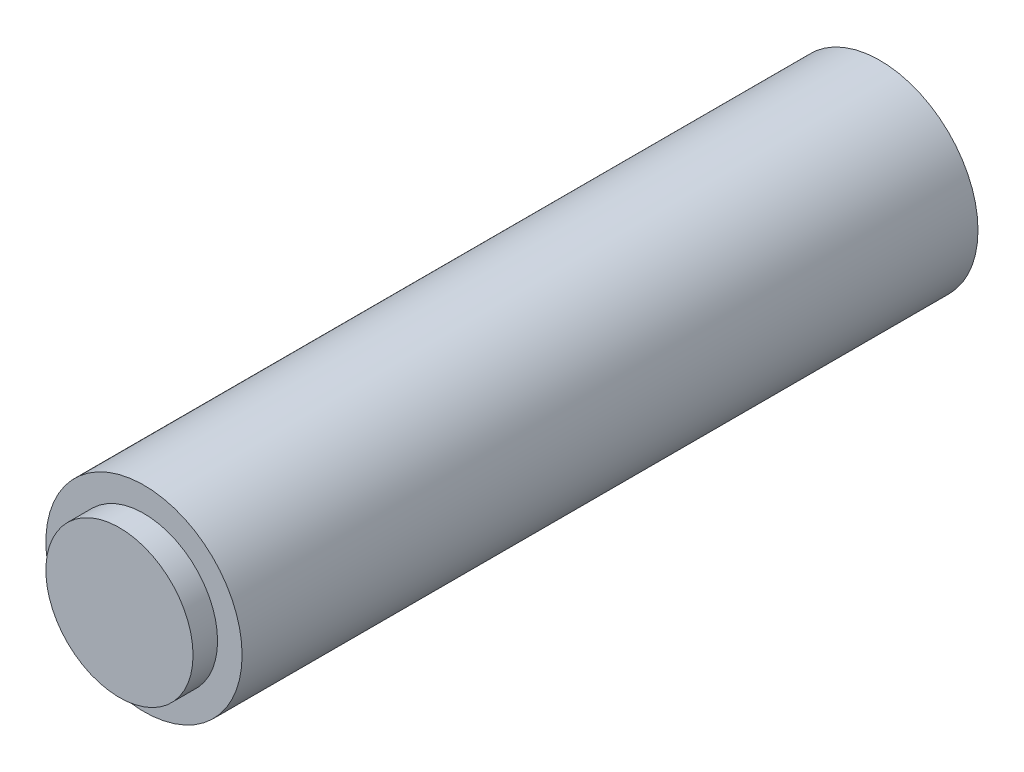
SolidWorks part; units mm, degrees
ref_plane "Спереди" through (0, 0, 0) normal (0, 0, 1) x (1, 0, 0)
ref_plane "Сверху" through (0, 0, 0) normal (0, 1, 0) x (1, 0, 0)
ref_plane "Справа" through (0, 0, 0) normal (1, 0, 0) x (0, 0, -1)
sketch "Эскиз1" plane through (0, 0, 0) normal (0, 0, 1) x (1, 0, 0)
  circle A0 centre (0, 0) radius 10
  dimension "D1" = 20
extrude "Бобышка-Вытянуть1" add sketch "Эскиз1" along normal blind 77.5
sketch "Эскиз2" plane through (0, 0, 77.5) normal (0, 0, 1) x (1, 0, 0)
  circle A0 centre (0, 0) radius 7.5
extrude "Вырез-Вытянуть1" cut sketch "Эскиз2" against normal blind 2.5 flip side to cut
